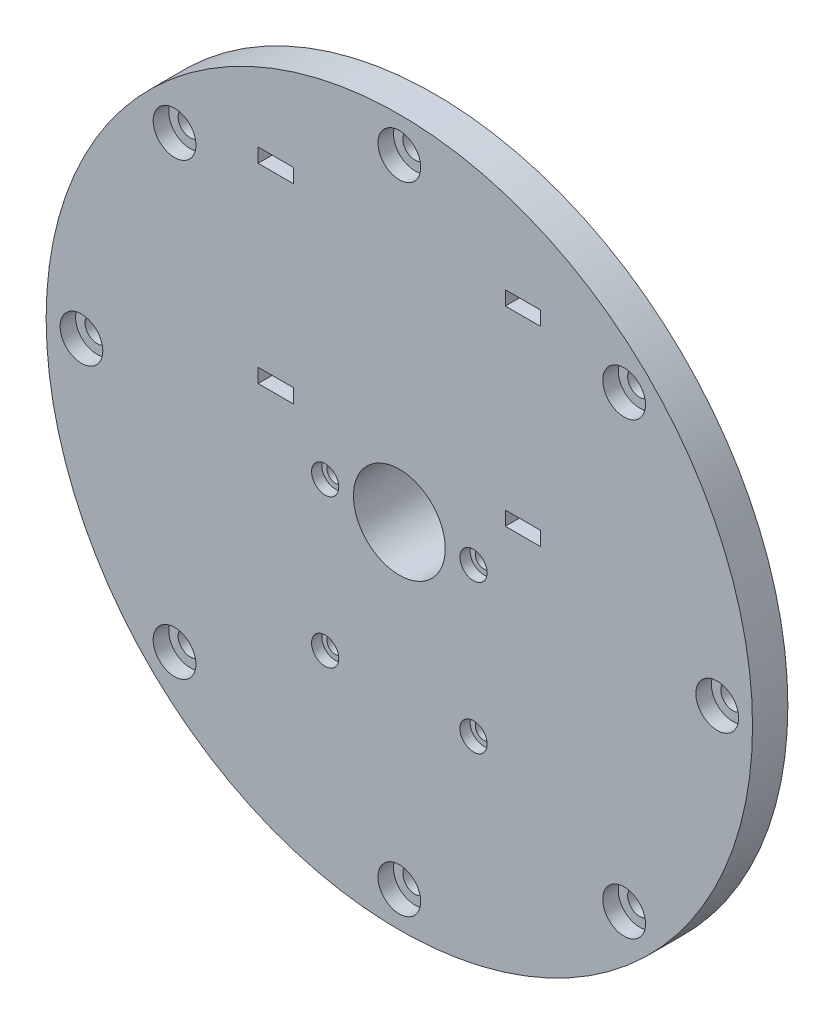
SolidWorks part; units mm, degrees
ref_plane "正面" through (0, 0, 0) normal (0, 0, 1) x (1, 0, 0)
ref_plane "平面" through (0, 0, 0) normal (0, 1, 0) x (1, 0, 0)
ref_plane "右側面" through (0, 0, 0) normal (1, 0, 0) x (0, 0, -1)
sketch "ｽｹｯﾁ1" plane through (0, 0, 0) normal (0, 0, 1) x (1, 0, 0)
  circle A0 centre (0, 0) radius 50
  dimension "D1" = 100
extrude "ﾎﾞｽ - 押し出し1" add sketch "ｽｹｯﾁ1" along normal blind 5
sketch "ｽｹｯﾁ8" plane through (0, 0, 0) normal (0, 0, -1) x (-1, 0, 0)
  line L1 (13, 8.88) -> (-13, 8.88)
  line L2 (13, 8.88) -> (13, -23.62)
  line L3 (13, -23.62) -> (-13, -23.62)
  line L4 (-13, 8.88) -> (-13, -23.62)
  point P4 (0, 8.88)
  dimension "D1" = 8.88
  dimension "D2" = 32.5
  dimension "D3" = 26
extrude "ﾎﾞｽ - 押し出し3" add sketch "ｽｹｯﾁ8" along normal blind 10
sketch "ｽｹｯﾁ6" plane through (0, 0, 5) normal (0, 0, 1) x (1, 0, 0)
  circle A0 centre (0, 0) radius 6.5
  dimension "D1" = 13
extrude "ｶｯﾄ - 押し出し1" cut sketch "ｽｹｯﾁ6" against normal through all
hole_wizard "M2 丸平ねじ用座ぐり穴1" positions "ｽｹｯﾁ2" profile "ｽｹｯﾁ3" counterbore size "M2" standard "JIS" end condition through all
sketch "ｽｹｯﾁ2" plane through (0, 0, 5) normal (0, 0, 1) x (1, 0, 0)
  point P0 (-10.5, 0)
  point P4 (-10.5, -21)
  dimension "D1" = 10.5
  dimension "D2" = 10.5
  dimension "D3" = 21
sketch "ｽｹｯﾁ3" plane through (-10.5, 0, 5) normal (1, 0, 0) x (0, -1, 0)
  line L0 (0, 0) -> (0, 15)
  line L1 (0, 15) -> (1.2, 15)
  line L3 (1.2, 15) -> (1.2, 1.45)
  line L4 (1.2, 1.45) -> (1.925, 1.45)
  line L5 (1.925, 1.45) -> (1.925, 0)
  line L7 (1.925, 0) -> (0, 0)
  line L11 (0, -6.35) -> (0, 107.95) construction
  dimension "通し穴の直径" = 2.4
  dimension "通し穴の深さ" = 15
  dimension "座ぐり穴の直径" = 3.85
  dimension "座ぐり穴の深さ" = 1.45
mirror "ﾐﾗｰ1" about plane through (0, 0, 0) normal (1, 0, 0) of "M2 丸平ねじ用座ぐり穴1"
hole_wizard "M3 丸平ねじ用座ぐり穴2" positions "ｽｹｯﾁ4" profile "ｽｹｯﾁ5" counterbore size "M3" standard "JIS" end condition through all
sketch "ｽｹｯﾁ4" plane through (0, 0, 5) normal (0, 0, 1) x (1, 0, 0)
  point P0 (45, 0)
  point P2 (45, 0)
  dimension "D1" = 45
sketch "ｽｹｯﾁ5" plane through (45, 0, 5) normal (1, 0, 0) x (0, -1, 0)
  line L0 (0, 0) -> (0, 15)
  line L1 (0, 15) -> (1.7, 15)
  line L3 (1.7, 15) -> (1.7, 2.2)
  line L4 (1.7, 2.2) -> (3.025, 2.2)
  line L5 (3.025, 2.2) -> (3.025, 0)
  line L7 (3.025, 0) -> (0, 0)
  line L11 (0, -6.35) -> (0, 107.95) construction
  dimension "通し穴の直径" = 3.4
  dimension "通し穴の深さ" = 15
  dimension "座ぐり穴の直径" = 6.05
  dimension "座ぐり穴の深さ" = 2.2
pattern_circular "円形ﾊﾟﾀｰﾝ1" count 8 every 45 about axis through (0, 0, 0) along (0, 0, 1) of "M3 丸平ねじ用座ぐり穴2"
sketch "ｽｹｯﾁ7" plane through (0, 0, 0) normal (0, 0, -1) x (-1, 0, 0)
  line L1 (28, 25) -> (25, 25)
  line L2 (28, 25) -> (28, 10)
  line L3 (28, 10) -> (25, 10)
  line L4 (25, 25) -> (25, 10)
  dimension "D1" = 3
  dimension "D2" = 15
  dimension "D3" = 10
  dimension "D4" = 25
extrude "ﾎﾞｽ - 押し出し2" add sketch "ｽｹｯﾁ7" along normal blind 3
fillet "ﾌｨﾚｯﾄ1" radius 1 1 edges at (-28, 17.5, 0)
mirror "ﾐﾗｰ2" about plane through (0, 0, 0) normal (1, 0, 0) of "ﾌｨﾚｯﾄ1", "ﾎﾞｽ - 押し出し2"
fillet "ﾌｨﾚｯﾄ2" radius 2.5 4 edges at (13, 8.88, -5) (13, -23.62, -5) (-13, -23.62, -5) (-13, 8.88, -5)
sketch "ｽｹｯﾁ10" plane through (0, 0, 0) normal (0, 0, -1) x (-1, 0, 0)
  line L0 (25, 25) -> (25, 10) construction
  line L1 (-25, 10) -> (25, 10)
  line L2 (-25, 10) -> (-25, 33)
  line L3 (-25, 33) -> (25, 33)
  line L4 (25, 10) -> (25, 33)
  dimension "D1" = 23
sketch "ｽｹｯﾁ9" plane through (0, 0, 0) normal (0, 0, -1) x (-1, 0, 0)
  line L0 (25, 10) -> (29, 10) construction
  line L1 (20, 36) -> (15, 36)
  line L2 (20, 36) -> (20, 34)
  line L3 (20, 34) -> (15, 34)
  line L4 (15, 36) -> (15, 34)
  line L5 (20, 9) -> (15, 9)
  line L6 (20, 9) -> (20, 7)
  line L7 (20, 7) -> (15, 7)
  line L8 (15, 9) -> (15, 7)
  line L13 (25, 25) -> (25, 10) construction
  line L14 (-25, 33) -> (25, 33) construction
  dimension "D1" = 1
  dimension "D2" = 5
  dimension "D3" = 2
  dimension "D4" = 5
  dimension "D5" = 1
extrude "ｶｯﾄ - 押し出し2" cut sketch "ｽｹｯﾁ9" against normal through all
mirror "ﾐﾗｰ3" about plane through (0, 0, 0) normal (1, 0, 0) of "ｶｯﾄ - 押し出し2"
